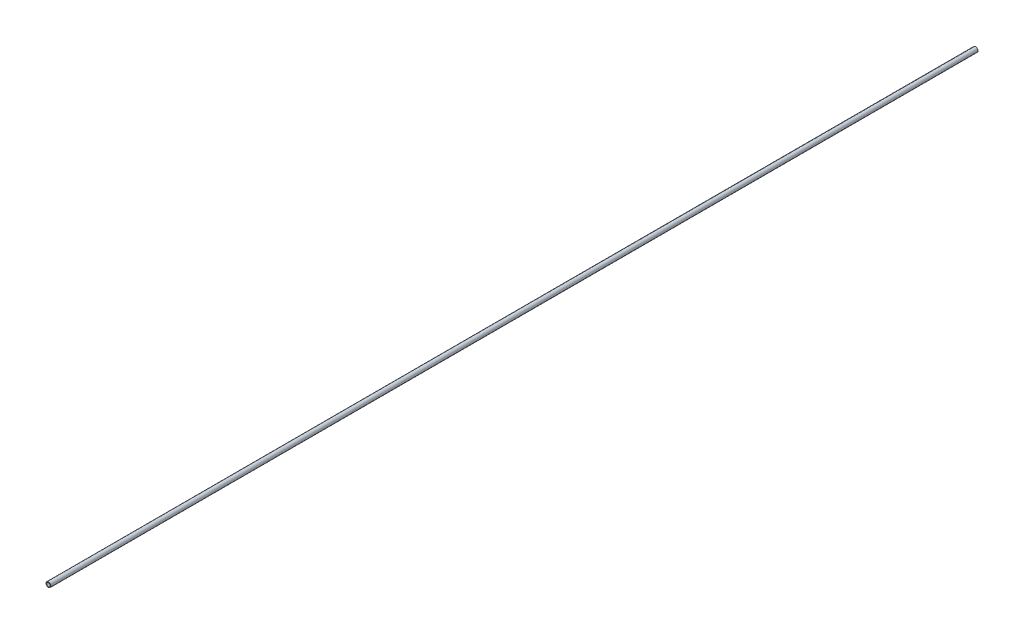
SolidWorks part; units mm, degrees
ref_plane "Front Plane" through (0, 0, 0) normal (0, 0, 1) x (1, 0, 0)
ref_plane "Top Plane" through (0, 0, 0) normal (0, 1, 0) x (1, 0, 0)
ref_plane "Right Plane" through (0, 0, 0) normal (1, 0, 0) x (0, 0, -1)
sketch "Sketch1" plane through (0, 0, 0) normal (0, 0, 1) x (1, 0, 0)
  circle A0 centre (0, 0) radius 6.35
  circle A1 centre (0, 0) radius 4.7625
  dimension "D1" = 9.525
  dimension "D2" = 12.7
extrude "Boss-Extrude1" add sketch "Sketch1" along normal blind 2438.4
